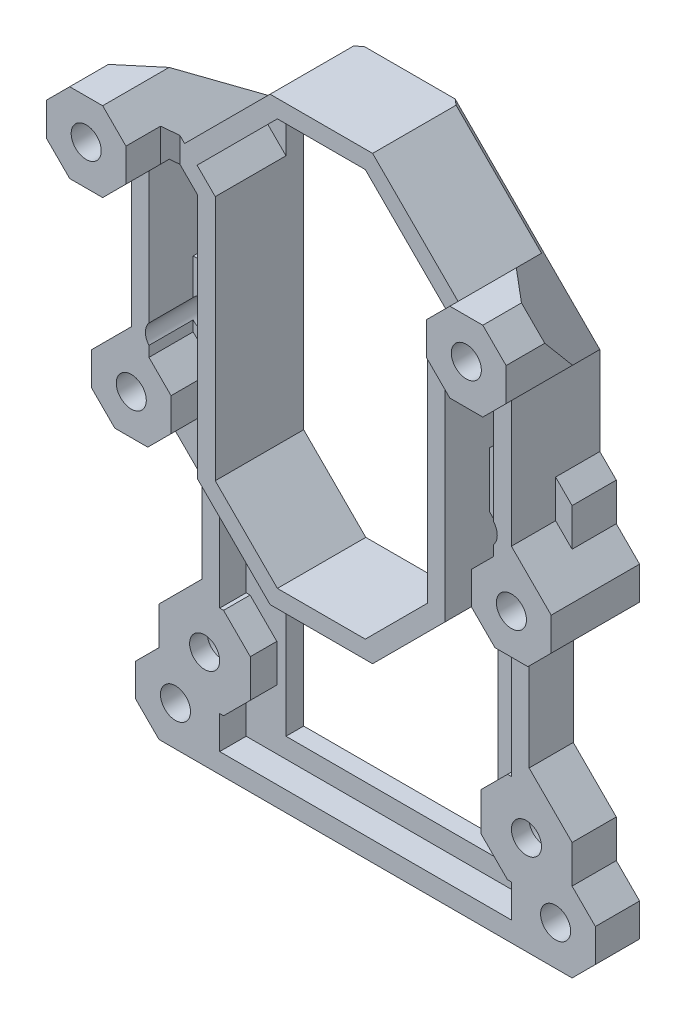
SolidWorks part; units mm, degrees
ref_plane "Front Plane" through (0, 0, 0) normal (0, 0, 1) x (1, 0, 0)
ref_plane "Top Plane" through (0, 0, 0) normal (0, 1, 0) x (1, 0, 0)
ref_plane "Right Plane" through (0, 0, 0) normal (1, 0, 0) x (0, 0, -1)
sketch "Sketch1" plane through (0, 0, 0) normal (0, 0, 1) x (1, 0, 0)
  line L0 (-21.5, 0) -> (21.5, 0) construction
  line L1 (21.5, 0) -> (21.5, 60) construction
  line L2 (21.5, 60) -> (-21.5, 60) construction
  line L3 (-21.5, 60) -> (-21.5, 0) construction
  line L4 (-21.5, 33) -> (21.5, 33) construction
  line L5 (0, 0) -> (0, 60) construction
  line L9 (-5.799, 20) -> (0, 20)
  line L12 (0, 60) -> (0, 76.4523) construction
  line L13 (0, 68) -> (-4.9706, 68)
  line L15 (-16.5, 34.364) -> (-16.5, 55) construction
  line L16 (-20.339, 11.8029) -> (-18.5, 13.6419)
  line L17 (-16.061, 11.8029) -> (-20.339, 11.8029)
  line L18 (-20.339, 11.8029) -> (-23.364, 8.778)
  line L19 (-23.364, 8.778) -> (-23.364, 4.5)
  line L20 (-23.364, 4.5) -> (-20.339, 1.475)
  line L21 (-20.339, 1.475) -> (-16.061, 1.475)
  line L23 (-13.036, 37.5) -> (-13.036, 41.778)
  line L24 (-13.036, 41.778) -> (-16.061, 44.8029)
  line L25 (-16.061, 44.8029) -> (-20.339, 44.8029)
  line L26 (-20.339, 44.8029) -> (-23.364, 41.778)
  line L27 (-23.364, 41.778) -> (-23.364, 37.5)
  line L28 (-23.364, 37.5) -> (-20.339, 34.475)
  line L29 (-20.339, 34.475) -> (-16.061, 34.475)
  line L30 (-16.061, 34.475) -> (-13.036, 37.5)
  line L31 (13.036, 37.5) -> (16.061, 34.475)
  line L32 (16.061, 34.475) -> (20.339, 34.475)
  line L33 (20.339, 34.475) -> (23.364, 37.5)
  line L34 (23.364, 37.5) -> (23.364, 41.778)
  line L35 (23.364, 41.778) -> (20.339, 44.8029)
  line L36 (20.339, 44.8029) -> (16.061, 44.8029)
  line L37 (16.061, 44.8029) -> (13.036, 41.778)
  line L38 (13.036, 41.778) -> (13.036, 37.5)
  line L39 (-14, 0) -> (-14, 51.1419) construction
  line L40 (-16.5, 0) -> (-16.5, 33.5294) construction
  line L41 (-17, 58.136) -> (-17, 61.864)
  line L42 (-17, 61.864) -> (-19.636, 64.5)
  line L43 (-19.636, 64.5) -> (-23.364, 64.5)
  line L44 (-23.364, 64.5) -> (-26, 61.864)
  line L45 (-26, 61.864) -> (-26, 58.136)
  line L46 (-26, 58.136) -> (-23.364, 55.5)
  line L47 (-23.364, 55.5) -> (-19.636, 55.5)
  line L48 (-19.636, 55.5) -> (-17, 58.136)
  line L49 (-23.364, 37.5) -> (-26, 34.864)
  line L50 (-26, 34.864) -> (-26, 31.136)
  line L51 (-26, 31.136) -> (-23.364, 28.5)
  line L52 (-23.364, 28.5) -> (-19.636, 28.5)
  line L53 (-19.636, 28.5) -> (-17, 31.136)
  line L54 (-17, 31.136) -> (-17, 34.864)
  line L55 (-17, 34.864) -> (-19.636, 37.5)
  line L56 (-19.636, 37.5) -> (-23.364, 37.5)
  line L57 (-23.364, 4.5) -> (-26, 1.864)
  line L58 (-26, 1.864) -> (-26, -1.864)
  line L59 (-26, -1.864) -> (-23.364, -4.5)
  line L60 (-23.364, -4.5) -> (-19.636, -4.5)
  line L61 (-19.636, -4.5) -> (-17, -1.864)
  line L62 (-17, -1.864) -> (-17, 1.864)
  line L63 (-17, 1.864) -> (-19.636, 4.5)
  line L64 (-19.636, 4.5) -> (-23.364, 4.5)
  line L65 (23.364, -4.5) -> (26, -1.864)
  line L66 (26, -1.864) -> (26, 1.864)
  line L67 (26, 1.864) -> (23.364, 4.5)
  line L68 (23.364, 4.5) -> (19.636, 4.5)
  line L69 (19.636, 4.5) -> (17, 1.864)
  line L70 (17, 1.864) -> (17, -1.864)
  line L71 (17, -1.864) -> (19.636, -4.5)
  line L72 (19.636, -4.5) -> (23.364, -4.5)
  line L73 (19.636, 28.5) -> (23.364, 28.5)
  line L74 (23.364, 28.5) -> (26, 31.136)
  line L75 (26, 31.136) -> (26, 34.864)
  line L76 (26, 34.864) -> (23.364, 37.5)
  line L77 (23.364, 37.5) -> (19.636, 37.5)
  line L78 (19.636, 37.5) -> (17, 34.864)
  line L79 (17, 34.864) -> (17, 31.136)
  line L80 (17, 31.136) -> (19.636, 28.5)
  line L81 (23.364, 64.5) -> (19.636, 64.5)
  line L82 (19.636, 64.5) -> (17, 61.864)
  line L83 (17, 61.864) -> (17, 58.136)
  line L84 (17, 58.136) -> (19.636, 55.5)
  line L85 (19.636, 55.5) -> (23.364, 55.5)
  line L86 (23.364, 55.5) -> (26, 58.136)
  line L87 (26, 58.136) -> (26, 61.864)
  line L88 (26, 61.864) -> (23.364, 64.5)
  line L89 (-12, 34) -> (-12, 68.1911) construction
  line L90 (12, 34) -> (12, 71.0139) construction
  line L91 (0, -4.5) -> (-19.636, -4.5)
  line L94 (0, -2.25) -> (-16.5, -2.25)
  line L95 (-16.5, -2.25) -> (-16.5, 34.364)
  line L97 (0, -4.5) -> (0, 0) construction
  line L100 (-4.9706, 22) -> (0, 22)
  line L101 (0, -2.25) -> (-16.5, -2.25) construction
  line L102 (-17, 61.864) -> (-12, 56.864)
  line L103 (-12, 56.864) -> (-12, 29.0294)
  line L105 (-4.9706, 68) -> (-14.0533, 58.9173)
  line L106 (-23.364, 55.5) -> (-21.5, 53.636)
  line L107 (-23.364, 37.5) -> (-21.5, 39.364)
  line L108 (-21.5, 39.364) -> (-21.5, 53.636)
  line L109 (-23.364, 4.5) -> (-18.5, 9.364)
  line L110 (-18.5, 9.364) -> (-18.5, 23.636)
  line L111 (-18.5, 23.636) -> (-23.364, 28.5)
  line L115 (-16.5, -4.5) -> (-16.5, 0) construction
  line L116 (-16.5503, 58.5858) -> (-14, 56.0355)
  line L117 (-14, 56.0355) -> (-14, 28.201)
  line L119 (-17, 34.864) -> (-16.5, 34.364)
  line L120 (-19.636, 37.5) -> (-19.5, 37.364)
  line L121 (-19.5, 37.364) -> (-19.5, 55.636)
  line L122 (-19.5, 55.636) -> (-19.636, 55.5)
  line L123 (-17, 58.136) -> (-16.5503, 58.5858)
  line L124 (-19.636, 55.5) -> (-19.5, 55.636)
  line L126 (-16.061, 1.475) -> (-13.036, 4.5)
  line L128 (-12, 50.5) -> (-33.4283, 71.9283) construction
  line L129 (0, 70) -> (-5.799, 70)
  line L130 (-5.799, 70) -> (-15.4675, 60.3315)
  line L131 (-4.9706, 22) -> (-12, 29.0294)
  line L132 (-12, 26.201) -> (-12, 0)
  line L133 (0, 0) -> (-12, 0)
  line L134 (-12, 26.201) -> (-5.799, 20)
  line L135 (-12, 26.201) -> (-14, 28.201)
  line L136 (-13.036, 4.5) -> (-13.036, 8.778)
  line L137 (-13.036, 8.778) -> (-16.061, 11.8029)
  circle A0 centre (-21.5, 60) radius 1.7
  circle A1 centre (-21.5, 33) radius 1.7
  circle A2 centre (-21.5, 0) radius 1.7
  circle A3 centre (21.5, 0) radius 1.7
  circle A4 centre (21.5, 33) radius 1.7
  circle A5 centre (21.5, 60) radius 1.7
  circle A7 centre (-18.2, 6.639) radius 1.7
  circle A8 centre (-18.2, 39.639) radius 1.7
  circle A9 centre (18.2, 39.639) radius 1.7
  circle A10 centre (0, 34) radius 12 construction
  circle A11 centre (0, 56) radius 12 construction
  circle A12 centre (-18.2, 39.639) radius 3
  circle A13 centre (-18.2, 39.639) radius 5.164 construction
  circle A14 centre (18.2, 39.639) radius 5.164 construction
  circle A15 centre (-21.5, 60) radius 4.5 construction
  circle A16 centre (-21.5, 33) radius 4.5 construction
  circle A17 centre (-21.5, 0) radius 4.5 construction
  circle A18 centre (21.5, 0) radius 4.5 construction
  circle A19 centre (21.5, 33) radius 4.5 construction
  circle A20 centre (21.5, 60) radius 4.5 construction
  circle A21 centre (-18.2, 6.639) radius 3
  circle A22 centre (-18.2, 6.639) radius 5.164 construction
  dimension "D4" = 3.4
  dimension "D5" = 24
  dimension "D7" = 2
  dimension "D8" = 6
  dimension "D9" = 9
  dimension "D10" = 9
  dimension "D11" = 9
  dimension "D12" = 9
  dimension "D13" = 9
  dimension "D14" = 9
  dimension "D1" = 43
  dimension "D2" = 33
  dimension "D3" = 27
  dimension "D15" = 2.5
  dimension "D16" = 2
  dimension "D17" = 2
  dimension "D19" = 135
  dimension "D20" = 2.25
  dimension "D21" = 2
  dimension "D22" = 2
  dimension "D23" = 2
  dimension "D24" = 34
  dimension "D25" = 2
  dimension "D26" = 22
  dimension "D27" = 2
  dimension "D28" = 2
sketch "Sketch5" plane through (0, 0, 0) normal (0, 0, 1) x (1, 0, 0)
  line L102 (0, -4.5) -> (-19.636, -4.5) construction
  line L103 (-23.364, -4.5) -> (-19.636, -4.5) construction
  line L104 (-26, -1.864) -> (-23.364, -4.5) construction
  line L105 (-26, 1.864) -> (-26, -1.864) construction
  line L106 (-23.364, 4.5) -> (-26, 1.864) construction
  line L107 (-23.364, 8.778) -> (-23.364, 4.5) construction
  line L108 (-20.339, 11.8029) -> (-23.364, 8.778) construction
  line L109 (-20.339, 11.8029) -> (-18.5, 13.6419) construction
  line L110 (-18.5, 9.364) -> (-18.5, 23.636) construction
  line L111 (-18.5, 23.636) -> (-23.364, 28.5) construction
  line L112 (-26, 31.136) -> (-23.364, 28.5) construction
  line L113 (-26, 34.864) -> (-26, 31.136) construction
  line L114 (-23.364, 37.5) -> (-26, 34.864) construction
  line L115 (-23.364, 41.778) -> (-23.364, 37.5) construction
  line L116 (-20.339, 44.8029) -> (-23.364, 41.778) construction
  line L117 (-21.5, 39.364) -> (-21.5, 53.636) construction
  line L118 (-23.364, 55.5) -> (-21.5, 53.636) construction
  line L119 (-26, 58.136) -> (-23.364, 55.5) construction
  line L120 (-26, 61.864) -> (-26, 58.136) construction
  line L121 (-23.364, 64.5) -> (-26, 61.864) construction
  line L122 (-19.636, 64.5) -> (-23.364, 64.5) construction
  line L123 (-17, 61.864) -> (-19.636, 64.5) construction
  line L124 (-17, 61.864) -> (-12, 56.864) construction
  line L125 (-5.799, 70) -> (-15.4675, 60.3315) construction
  line L126 (0, 70) -> (-5.799, 70) construction
  line L127 (0, 68) -> (-4.9706, 68) construction
  line L128 (-4.9706, 68) -> (-14.0533, 58.9173) construction
  line L129 (-12, 56.864) -> (-12, 29.0294) construction
  line L130 (-4.9706, 22) -> (-12, 29.0294) construction
  line L131 (-4.9706, 22) -> (0, 22) construction
  line L132 (-5.799, 20) -> (0, 20) construction
  line L133 (-12, 26.201) -> (-5.799, 20) construction
  line L134 (-12, 26.201) -> (-12, 0) construction
  line L135 (0, 0) -> (-12, 0) construction
  line L136 (0, 0) -> (0, 60) construction
  line L137 (0, 60) -> (0, 76.4523) construction
  line L138 (0, -4.5) -> (0, 0) construction
  line L139 (19.636, -4.5) -> (-19.636, -4.5)
  line L140 (-23.364, -4.5) -> (-19.636, -4.5)
  line L141 (-26, -1.864) -> (-23.364, -4.5)
  line L142 (-26, 1.864) -> (-26, -1.864)
  line L143 (-23.364, 4.5) -> (-26, 1.864)
  line L144 (-23.364, 8.778) -> (-23.364, 4.5)
  line L145 (-20.339, 11.8029) -> (-23.364, 8.778)
  line L146 (-20.339, 11.8029) -> (-18.5, 13.6419)
  line L147 (-18.5, 13.6419) -> (-18.5, 23.636)
  line L148 (-18.5, 23.636) -> (-23.364, 28.5)
  line L149 (-26, 31.136) -> (-23.364, 28.5)
  line L150 (-26, 34.864) -> (-26, 31.136)
  line L151 (-23.364, 37.5) -> (-26, 34.864)
  line L152 (-23.364, 41.778) -> (-23.364, 37.5)
  line L153 (-21.5, 43.6419) -> (-23.364, 41.778)
  line L154 (-21.5, 43.6419) -> (-21.5, 53.636)
  line L155 (-23.364, 55.5) -> (-21.5, 53.636)
  line L156 (-26, 58.136) -> (-23.364, 55.5)
  line L157 (-26, 61.864) -> (-26, 58.136)
  line L158 (-23.364, 64.5) -> (-26, 61.864)
  line L159 (-19.636, 64.5) -> (-23.364, 64.5)
  line L160 (-17, 61.864) -> (-19.636, 64.5)
  line L161 (-17, 61.864) -> (-15.4675, 60.3315)
  line L162 (-5.799, 70) -> (-15.4675, 60.3315)
  line L163 (5.799, 70) -> (-5.799, 70)
  line L164 (4.9706, 68) -> (-4.9706, 68)
  line L165 (-4.9706, 68) -> (-12, 60.9706)
  line L166 (-12, 34) -> (-12, 29.0294)
  line L167 (-4.9706, 22) -> (-12, 29.0294)
  line L168 (-4.9706, 22) -> (4.9706, 22)
  line L169 (-5.799, 20) -> (5.799, 20)
  line L170 (-12, 26.201) -> (-5.799, 20)
  line L171 (-12, 26.201) -> (-12, 0)
  line L172 (12, 0) -> (-12, 0)
  line L173 (0, 0) -> (0, 60) construction
  line L174 (0, 60) -> (0, 76.4523) construction
  line L175 (0, -4.5) -> (0, 0) construction
  line L176 (12, 56.864) -> (12, 60.9706)
  line L177 (-12, 34) -> (-12, 68.1911) construction
  line L178 (-12, 34) -> (-12, 60.9706)
  line L179 (12, 26.201) -> (12, 0)
  line L180 (12, 26.201) -> (5.799, 20)
  line L181 (4.9706, 22) -> (12, 29.0294)
  line L182 (12, 56.864) -> (12, 29.0294)
  line L183 (4.9706, 68) -> (12, 60.9706)
  line L184 (5.799, 70) -> (15.4675, 60.3315)
  line L185 (17, 61.864) -> (15.4675, 60.3315)
  line L186 (17, 61.864) -> (19.636, 64.5)
  line L187 (19.636, 64.5) -> (23.364, 64.5)
  line L188 (23.364, 64.5) -> (26, 61.864)
  line L189 (26, 61.864) -> (26, 58.136)
  line L190 (26, 58.136) -> (23.364, 55.5)
  line L191 (23.364, 55.5) -> (21.5, 53.636)
  line L192 (21.5, 43.6419) -> (21.5, 53.636)
  line L193 (21.5, 43.6419) -> (23.364, 41.778)
  line L194 (23.364, 41.778) -> (23.364, 37.5)
  line L195 (23.364, 37.5) -> (26, 34.864)
  line L196 (26, 34.864) -> (26, 31.136)
  line L197 (26, 31.136) -> (23.364, 28.5)
  line L198 (18.5, 23.636) -> (23.364, 28.5)
  line L199 (18.5, 13.6419) -> (18.5, 23.636)
  line L200 (20.339, 11.8029) -> (18.5, 13.6419)
  line L201 (20.339, 11.8029) -> (23.364, 8.778)
  line L202 (23.364, 8.778) -> (23.364, 4.5)
  line L203 (23.364, 4.5) -> (26, 1.864)
  line L204 (26, 1.864) -> (26, -1.864)
  line L205 (26, -1.864) -> (23.364, -4.5)
  line L206 (23.364, -4.5) -> (19.636, -4.5)
  circle A8 centre (-18.2, 39.639) radius 1.7 construction
  circle A9 centre (-18.2, 6.639) radius 1.7 construction
  circle A10 centre (-18.2, 39.639) radius 1.7
  circle A11 centre (-18.2, 6.639) radius 1.7
  circle A12 centre (18.2, 6.639) radius 1.7
  circle A13 centre (18.2, 39.639) radius 1.7
extrude "Boss-Extrude1" add sketch "Sketch5" along normal blind 2
sketch "Sketch9" plane through (0, 0, 2) normal (0, 0, 1) x (1, 0, 0)
  line L73 (0, 70) -> (-5.799, 70) construction
  line L76 (0, 60) -> (0, 76.4523) construction
  line L77 (0, 0) -> (0, 60) construction
  line L78 (0, -4.5) -> (0, 0) construction
  line L79 (0, 68) -> (-4.9706, 68) construction
  line L80 (-4.9706, 68) -> (-14.0533, 58.9173) construction
  line L81 (-5.799, 70) -> (-15.4675, 60.3315) construction
  line L82 (-17, 61.864) -> (-12, 56.864) construction
  line L83 (-17, 61.864) -> (-19.636, 64.5) construction
  line L84 (-19.636, 64.5) -> (-23.364, 64.5) construction
  line L85 (-23.364, 64.5) -> (-26, 61.864) construction
  line L86 (-26, 61.864) -> (-26, 58.136) construction
  line L87 (-26, 58.136) -> (-23.364, 55.5) construction
  line L88 (-23.364, 55.5) -> (-21.5, 53.636) construction
  line L89 (-21.5, 39.364) -> (-21.5, 53.636) construction
  line L90 (-20.339, 44.8029) -> (-23.364, 41.778) construction
  line L91 (-23.364, 41.778) -> (-23.364, 37.5) construction
  line L92 (-23.364, 37.5) -> (-26, 34.864) construction
  line L93 (-26, 34.864) -> (-26, 31.136) construction
  line L94 (-26, 31.136) -> (-23.364, 28.5) construction
  line L95 (-18.5, 23.636) -> (-23.364, 28.5) construction
  line L97 (-20.339, 11.8029) -> (-18.5, 13.6419) construction
  line L98 (-20.339, 11.8029) -> (-23.364, 8.778) construction
  line L99 (-23.364, 8.778) -> (-23.364, 4.5) construction
  line L100 (-23.364, 4.5) -> (-26, 1.864) construction
  line L101 (-26, 1.864) -> (-26, -1.864) construction
  line L102 (-26, -1.864) -> (-23.364, -4.5) construction
  line L103 (-23.364, -4.5) -> (-19.636, -4.5) construction
  line L104 (0, -2.25) -> (-16.5, -2.25) construction
  line L105 (-16.5, -2.25) -> (-16.5, 34.364) construction
  line L106 (-12, 26.201) -> (-5.799, 20) construction
  line L107 (-5.799, 20) -> (0, 20) construction
  line L108 (-4.9706, 22) -> (0, 22) construction
  line L109 (-4.9706, 22) -> (-12, 29.0294) construction
  line L110 (-12, 26.201) -> (-14, 28.201) construction
  line L111 (-14, 56.0355) -> (-14, 28.201) construction
  line L112 (-12, 56.864) -> (-12, 29.0294) construction
  line L113 (-16.5503, 58.5858) -> (-14, 56.0355) construction
  line L114 (-17, 58.136) -> (-16.5503, 58.5858) construction
  line L115 (-19.636, 55.5) -> (-17, 58.136) construction
  line L117 (5.799, 70) -> (-5.799, 70)
  line L118 (0, 60) -> (0, 76.4523) construction
  line L119 (0, 0) -> (0, 60) construction
  line L120 (0, -4.5) -> (0, 0) construction
  line L121 (4.9706, 68) -> (-4.9706, 68)
  line L122 (-4.9706, 68) -> (-14.0533, 58.9173)
  line L123 (-5.799, 70) -> (-15.4675, 60.3315)
  line L124 (-17, 61.864) -> (-15.4675, 60.3315)
  line L127 (-17, 61.864) -> (-19.636, 64.5)
  line L128 (-19.636, 64.5) -> (-23.364, 64.5)
  line L129 (-23.364, 64.5) -> (-26, 61.864)
  line L130 (-26, 61.864) -> (-26, 58.136)
  line L131 (-26, 58.136) -> (-23.364, 55.5)
  line L132 (-23.364, 55.5) -> (-21.5, 53.636)
  line L133 (-21.5, 43.6419) -> (-21.5, 53.636)
  line L134 (-21.5, 43.6419) -> (-23.364, 41.778)
  line L135 (-23.364, 41.778) -> (-23.364, 37.5)
  line L136 (-23.364, 37.5) -> (-26, 34.864)
  line L137 (-26, 34.864) -> (-26, 31.136)
  line L138 (-26, 31.136) -> (-23.364, 28.5)
  line L139 (-18.5, 23.636) -> (-23.364, 28.5)
  line L140 (18.5, 13.6419) -> (18.5, 23.636)
  line L141 (-20.339, 11.8029) -> (-18.5, 13.6419)
  line L142 (-20.339, 11.8029) -> (-23.364, 8.778)
  line L143 (-23.364, 8.778) -> (-23.364, 4.5)
  line L144 (-23.364, 4.5) -> (-26, 1.864)
  line L145 (-26, 1.864) -> (-26, -1.864)
  line L146 (-26, -1.864) -> (-23.364, -4.5)
  line L147 (-23.364, -4.5) -> (-19.636, -4.5)
  line L149 (16.5, -2.25) -> (-16.5, -2.25)
  line L150 (-16.5, -2.25) -> (-16.5, 1.475)
  line L151 (-12, 26.201) -> (-5.799, 20)
  line L152 (-5.799, 20) -> (5.799, 20)
  line L153 (-4.9706, 22) -> (4.9706, 22)
  line L154 (-4.9706, 22) -> (-12, 29.0294)
  line L155 (-12, 26.201) -> (-14, 28.201)
  line L156 (-14, 56.0355) -> (-14, 42.7419)
  line L157 (-12, 56.864) -> (-12, 29.0294)
  line L158 (-16.5503, 58.5858) -> (-14, 56.0355)
  line L159 (-17, 58.136) -> (-16.5503, 58.5858)
  line L160 (-19.5, 55.636) -> (-17, 58.136)
  line L161 (-14, 36.536) -> (-14, 28.201)
  line L162 (-16.061, 44.8029) -> (-20.339, 44.8029) construction
  line L163 (-13.036, 41.778) -> (-16.061, 44.8029) construction
  line L164 (-16.061, 34.475) -> (-13.036, 37.5) construction
  line L165 (-20.339, 34.475) -> (-16.061, 34.475) construction
  line L166 (-16.061, 11.8029) -> (-20.339, 11.8029) construction
  line L167 (-13.036, 8.778) -> (-16.061, 11.8029) construction
  line L168 (-13.036, 4.5) -> (-13.036, 8.778) construction
  line L169 (-16.061, 1.475) -> (-13.036, 4.5) construction
  line L170 (-20.339, 1.475) -> (-16.061, 1.475) construction
  line L171 (-16.061, 44.8029) -> (-19.5, 44.8029)
  line L172 (-14, 42.7419) -> (-16.061, 44.8029)
  line L173 (-16.061, 34.475) -> (-14, 36.536)
  line L174 (-16.5, 34.475) -> (-16.061, 34.475)
  line L175 (-16.061, 11.8029) -> (-16.5, 11.8029)
  line L176 (-13.036, 8.778) -> (-16.061, 11.8029)
  line L177 (-13.036, 4.5) -> (-13.036, 8.778)
  line L178 (-16.061, 1.475) -> (-13.036, 4.5)
  line L179 (-16.5, 1.475) -> (-16.061, 1.475)
  line L180 (-14.0533, 58.9173) -> (-12, 56.864)
  line L181 (-19.5, 44.8029) -> (-19.5, 55.636)
  line L182 (-16.5, 11.8029) -> (-16.5, 34.475)
  line L183 (16.5, 11.8029) -> (16.5, 34.475)
  line L184 (-18.5, 13.6419) -> (-18.5, 23.636)
  line L185 (19.5, 44.8029) -> (19.5, 55.636)
  line L186 (14.0533, 58.9173) -> (12, 56.864)
  line L187 (16.5, 1.475) -> (16.061, 1.475)
  line L188 (16.061, 1.475) -> (13.036, 4.5)
  line L189 (13.036, 4.5) -> (13.036, 8.778)
  line L190 (13.036, 8.778) -> (16.061, 11.8029)
  line L191 (16.061, 11.8029) -> (16.5, 11.8029)
  line L192 (16.5, 34.475) -> (16.061, 34.475)
  line L193 (16.061, 34.475) -> (14, 36.536)
  line L194 (14, 42.7419) -> (16.061, 44.8029)
  line L195 (16.061, 44.8029) -> (19.5, 44.8029)
  line L196 (14, 36.536) -> (14, 28.201)
  line L197 (19.5, 55.636) -> (17, 58.136)
  line L198 (17, 58.136) -> (16.5503, 58.5858)
  line L199 (16.5503, 58.5858) -> (14, 56.0355)
  line L200 (12, 56.864) -> (12, 29.0294)
  line L201 (14, 56.0355) -> (14, 42.7419)
  line L202 (12, 26.201) -> (14, 28.201)
  line L203 (4.9706, 22) -> (12, 29.0294)
  line L204 (12, 26.201) -> (5.799, 20)
  line L205 (16.5, -2.25) -> (16.5, 1.475)
  line L206 (23.364, -4.5) -> (19.636, -4.5)
  line L207 (26, -1.864) -> (23.364, -4.5)
  line L208 (26, 1.864) -> (26, -1.864)
  line L209 (23.364, 4.5) -> (26, 1.864)
  line L210 (23.364, 8.778) -> (23.364, 4.5)
  line L211 (20.339, 11.8029) -> (23.364, 8.778)
  line L212 (20.339, 11.8029) -> (18.5, 13.6419)
  line L213 (18.5, 23.636) -> (23.364, 28.5)
  line L214 (26, 31.136) -> (23.364, 28.5)
  line L215 (26, 34.864) -> (26, 31.136)
  line L216 (23.364, 37.5) -> (26, 34.864)
  line L217 (23.364, 41.778) -> (23.364, 37.5)
  line L218 (21.5, 43.6419) -> (23.364, 41.778)
  line L219 (21.5, 43.6419) -> (21.5, 53.636)
  line L220 (23.364, 55.5) -> (21.5, 53.636)
  line L221 (26, 58.136) -> (23.364, 55.5)
  line L222 (26, 61.864) -> (26, 58.136)
  line L223 (23.364, 64.5) -> (26, 61.864)
  line L224 (19.636, 64.5) -> (23.364, 64.5)
  line L225 (17, 61.864) -> (19.636, 64.5)
  line L226 (17, 61.864) -> (15.4675, 60.3315)
  line L227 (5.799, 70) -> (15.4675, 60.3315)
  line L228 (4.9706, 68) -> (14.0533, 58.9173)
  line L229 (0, -4.5) -> (-19.636, -4.5) construction
  line L230 (19.636, -4.5) -> (-19.636, -4.5)
  circle A2 centre (-21.5, 0) radius 1.7 construction
  circle A5 centre (-21.5, 33) radius 1.7 construction
  circle A6 centre (-18.2, 39.639) radius 1.7 construction
  circle A7 centre (-18.2, 6.639) radius 1.7 construction
  circle A10 centre (-21.5, 0) radius 1.7
  circle A12 centre (-21.5, 33) radius 1.7
  circle A13 centre (-18.2, 39.639) radius 1.7
  circle A14 centre (-18.2, 6.639) radius 1.7
  circle A15 centre (18.2, 6.639) radius 1.7
  circle A16 centre (18.2, 39.639) radius 1.7
  circle A17 centre (21.5, 33) radius 1.7
  circle A18 centre (21.5, 0) radius 1.7
extrude "Boss-Extrude3" add sketch "Sketch9" along normal blind 3
sketch "Sketch10" plane through (0, 0, 5) normal (0, 0, 1) x (1, 0, 0)
  line L0 (19.5, 40.7344) -> (19.5, 55.636)
  line L1 (-19.5, 40.7344) -> (-19.5, 55.636)
  line L21 (0, 68) -> (-4.9706, 68) construction
  line L30 (0, 60) -> (0, 76.4523) construction
  line L31 (0, 0) -> (0, 60) construction
  line L32 (0, -4.5) -> (0, 0) construction
  line L33 (-4.9706, 68) -> (-14.0533, 58.9173) construction
  line L34 (-17, 61.864) -> (-12, 56.864) construction
  line L35 (-12, 56.864) -> (-12, 29.0294) construction
  line L36 (-4.9706, 22) -> (-12, 29.0294) construction
  line L37 (-4.9706, 22) -> (0, 22) construction
  line L38 (-5.799, 20) -> (0, 20) construction
  line L39 (-12, 26.201) -> (-5.799, 20) construction
  line L40 (-12, 26.201) -> (-14, 28.201) construction
  line L41 (-14, 56.0355) -> (-14, 28.201) construction
  line L42 (-16.5503, 58.5858) -> (-14, 56.0355) construction
  line L43 (-17, 61.864) -> (-19.636, 64.5) construction
  line L45 (-19.636, 64.5) -> (-23.364, 64.5) construction
  line L46 (-23.364, 64.5) -> (-26, 61.864) construction
  line L47 (-26, 61.864) -> (-26, 58.136) construction
  line L48 (-26, 58.136) -> (-23.364, 55.5) construction
  line L50 (4.9706, 68) -> (-4.9706, 68)
  line L52 (0, 60) -> (0, 76.4523) construction
  line L53 (0, 0) -> (0, 60) construction
  line L54 (0, -4.5) -> (0, 0) construction
  line L58 (-4.9706, 68) -> (-14.0533, 58.9173)
  line L61 (-12, 56.864) -> (-12, 29.0294)
  line L62 (-4.9706, 22) -> (-12, 29.0294)
  line L63 (-4.9706, 22) -> (4.9706, 22)
  line L64 (-5.799, 20) -> (5.799, 20)
  line L65 (-12, 26.201) -> (-5.799, 20)
  line L66 (-12, 26.201) -> (-14, 28.201)
  line L67 (-14, 56.0355) -> (-14, 28.201)
  line L68 (-16.5503, 58.5858) -> (-14, 56.0355)
  line L69 (-17, 61.864) -> (-19.636, 64.5)
  line L70 (-19.636, 64.5) -> (-23.364, 64.5)
  line L71 (-23.364, 64.5) -> (-26, 61.864)
  line L72 (-26, 61.864) -> (-26, 58.136)
  line L73 (-26, 58.136) -> (-23.364, 55.5)
  line L74 (-17, 34.864) -> (-19.636, 37.5) construction
  line L75 (-23.364, 55.5) -> (-21.5, 53.636) construction
  line L76 (-21.5, 39.364) -> (-21.5, 53.636) construction
  line L79 (-23.364, 37.5) -> (-26, 34.864) construction
  line L80 (-26, 34.864) -> (-26, 31.136) construction
  line L81 (-26, 31.136) -> (-23.364, 28.5) construction
  line L82 (-23.364, 28.5) -> (-19.636, 28.5) construction
  line L83 (-19.636, 28.5) -> (-17, 31.136) construction
  line L84 (-17, 31.136) -> (-17, 34.864) construction
  line L85 (-23.364, 55.5) -> (-21.5, 53.636)
  line L86 (21.5, 39.364) -> (21.5, 53.636)
  line L87 (23.364, 37.5) -> (21.5, 39.364)
  line L89 (-23.364, 37.5) -> (-26, 34.864)
  line L90 (-26, 34.864) -> (-26, 31.136)
  line L91 (-26, 31.136) -> (-23.364, 28.5)
  line L92 (-23.364, 28.5) -> (-19.636, 28.5)
  line L93 (-19.636, 28.5) -> (-17, 31.136)
  line L94 (-17, 31.136) -> (-17, 34.864)
  line L95 (-19.5, 37.364) -> (-19.5, 55.636) construction
  line L96 (-19.636, 55.5) -> (-17, 58.136) construction
  line L97 (-17, 58.136) -> (-16.5503, 58.5858) construction
  line L98 (-17, 34.864) -> (-19.5, 37.364)
  line L99 (-19.5, 37.364) -> (-19.5, 38.5435)
  line L100 (-19.5, 55.636) -> (-17, 58.136)
  line L101 (-17, 58.136) -> (-16.5503, 58.5858)
  line L102 (0, 70) -> (-5.799, 70) construction
  line L103 (-5.799, 70) -> (-15.4675, 60.3315) construction
  line L104 (5.799, 70) -> (-5.799, 70)
  line L105 (-5.799, 70) -> (-15.4675, 60.3315)
  line L106 (-17, 61.864) -> (-15.4675, 60.3315)
  line L107 (-14.0533, 58.9173) -> (-12, 56.864)
  line L108 (-23.364, 37.5) -> (-21.5, 39.364) construction
  line L109 (-23.364, 37.5) -> (-21.5, 39.364)
  line L110 (-21.5, 39.364) -> (-21.5, 53.636)
  line L111 (17, 61.864) -> (15.4675, 60.3315)
  line L112 (5.799, 70) -> (15.4675, 60.3315)
  line L113 (17, 58.136) -> (16.5503, 58.5858)
  line L114 (19.5, 55.636) -> (17, 58.136)
  line L115 (19.5, 37.364) -> (19.5, 38.5435)
  line L116 (17, 34.864) -> (19.5, 37.364)
  line L117 (17, 31.136) -> (17, 34.864)
  line L118 (19.636, 28.5) -> (17, 31.136)
  line L119 (23.364, 28.5) -> (19.636, 28.5)
  line L120 (26, 31.136) -> (23.364, 28.5)
  line L121 (26, 34.864) -> (26, 31.136)
  line L122 (23.364, 37.5) -> (26, 34.864)
  line L123 (23.364, 55.5) -> (21.5, 53.636)
  line L124 (26, 58.136) -> (23.364, 55.5)
  line L125 (26, 61.864) -> (26, 58.136)
  line L126 (23.364, 64.5) -> (26, 61.864)
  line L127 (19.636, 64.5) -> (23.364, 64.5)
  line L128 (17, 61.864) -> (19.636, 64.5)
  line L129 (16.5503, 58.5858) -> (14, 56.0355)
  line L130 (14, 56.0355) -> (14, 28.201)
  line L131 (12, 26.201) -> (14, 28.201)
  line L132 (12, 26.201) -> (5.799, 20)
  line L133 (4.9706, 22) -> (12, 29.0294)
  line L134 (12, 56.864) -> (12, 29.0294)
  line L135 (14.0533, 58.9173) -> (12, 56.864)
  line L136 (4.9706, 68) -> (14.0533, 58.9173)
  circle A0 centre (-18.2, 39.639) radius 1.7 construction
  circle A1 centre (-21.5, 33) radius 1.7 construction
  circle A2 centre (-21.5, 33) radius 1.7
  circle A3 centre (21.5, 33) radius 1.7
  arc A4 (-19.5, 40.7344) -> (-19.5, 38.5435) centre (-18.2, 39.639) ccw
  circle A5 centre (18.2, 39.639) radius 1.7 construction
  arc A6 (19.5, 38.5435) -> (19.5, 40.7344) centre (18.2, 39.639) ccw
extrude "Boss-Extrude4" add sketch "Sketch10" along normal blind 5
sketch "Sketch12" plane through (0, 0, 10) normal (0, 0, 1) x (1, 0, 0)
  line L0 (-26, 58.136) -> (-23.364, 55.5) construction
  line L1 (-26, 61.864) -> (-26, 58.136) construction
  line L2 (-23.364, 64.5) -> (-26, 61.864) construction
  line L3 (-19.636, 64.5) -> (-23.364, 64.5) construction
  line L4 (-17, 61.864) -> (-19.636, 64.5) construction
  line L5 (-17, 58.136) -> (-17, 61.864) construction
  line L6 (-19.636, 55.5) -> (-17, 58.136) construction
  line L7 (-23.364, 55.5) -> (-19.636, 55.5) construction
  line L8 (-26, 58.136) -> (-23.364, 55.5)
  line L9 (-26, 61.864) -> (-26, 58.136)
  line L10 (-23.364, 64.5) -> (-26, 61.864)
  line L11 (-19.636, 64.5) -> (-23.364, 64.5)
  line L12 (-17, 61.864) -> (-19.636, 64.5)
  line L13 (-17, 58.136) -> (-17, 61.864)
  line L14 (-19.636, 55.5) -> (-17, 58.136)
  line L15 (-23.364, 55.5) -> (-19.636, 55.5)
  line L16 (0, 0) -> (0, 60) construction
  line L17 (0, 0) -> (0, 60) construction
  line L18 (17, 58.136) -> (17, 61.864)
  line L19 (17, 61.864) -> (19.636, 64.5)
  line L20 (19.636, 64.5) -> (23.364, 64.5)
  line L21 (23.364, 64.5) -> (26, 61.864)
  line L22 (26, 61.864) -> (26, 58.136)
  line L23 (26, 58.136) -> (23.364, 55.5)
  line L24 (23.364, 55.5) -> (19.636, 55.5)
  line L25 (19.636, 55.5) -> (17, 58.136)
extrude "Boss-Extrude5" add sketch "Sketch12" along normal blind 5.1
ref_plane "Plane1" through (19.25, 19.25, 0) normal (0.7071, 0.7071, 0) x (0, 0, -1)
ref_plane "Plane2" through (-19.25, 19.25, 0) normal (-0.7071, 0.7071, 0) x (0, 0, 1)
sketch "Sketch13" plane through (0, 0, 15.1) normal (0, 0, 1) x (1, 0, 0)
  line L0 (0, 0) -> (0, 60) construction
  line L1 (0, 0) -> (0, 60) construction
  circle A0 centre (-21.5, 60) radius 1.7 construction
  circle A1 centre (-21.5, 60) radius 1.7
  circle A2 centre (21.5, 60) radius 1.7
extrude "Suspension Dowels" cut sketch "Sketch13" against normal blind 3.75
sketch "Sketch15" plane through (19.25, 19.25, 0) normal (0.7071, 0.7071, 0) x (0, 0, -1)
  line L0 (0, 53.1292) -> (-15.3209, 65.985)
  line L1 (-15.3209, 65.985) -> (-8.893, 73.6454)
  line L2 (-8.893, 73.6454) -> (6.4279, 60.7896)
  line L3 (6.4279, 60.7896) -> (0, 53.1292)
  line L4 (0, 44.1942) -> (0, 74.4983) construction
  dimension "D1" = 20
  dimension "D2" = 10
  dimension "D3" = 50
extrude "Top Angle 1" cut sketch "Sketch15" against normal mid plane 50
sketch "Sketch16" plane through (-19.25, 19.25, 0) normal (-0.7071, 0.7071, 0) x (0, 0, 1)
  line L0 (0, 53.1292) -> (15.3209, 65.985)
  line L1 (15.3209, 65.985) -> (8.893, 73.6454)
  line L2 (8.893, 73.6454) -> (-6.4279, 60.7896)
  line L3 (-6.4279, 60.7896) -> (0, 53.1292)
  line L7 (0, 55.7652) -> (0, 59.4932) construction
  dimension "D1" = 50
  dimension "D2" = 20
  dimension "D3" = 10
extrude "Top Angle 2" cut sketch "Sketch16" against normal mid plane 50
chamfer "Chamfer1" distance 1 angle 50 8 edges at (18.0251, 57.1109, 2) (-18.0251, 57.1109, 2) (17, 60, 10) (-17, 60, 10) (21.5, 55.5, 10) (-21.5, 55.5, 10) (21.5, 28.5, 5) (-21.5, 28.5, 5)
sketch "Sketch18" plane through (0, 0, 0) normal (0, 0, -1) x (-1, 0, 0)
  line L0 (0, 0) -> (0, 60) construction
  line L1 (0, 0) -> (0, 60) construction
  circle A0 centre (18.2, 39.639) radius 3 construction
  circle A1 centre (18.2, 6.639) radius 3 construction
  circle A2 centre (18.2, 39.639) radius 3
  circle A3 centre (18.2, 6.639) radius 3
  circle A4 centre (-18.2, 39.639) radius 3
  circle A5 centre (-18.2, 6.639) radius 3
extrude "M3 Head Holes" cut sketch "Sketch18" against normal blind 3
ref_plane "Print Support Plane" through (0, 0, 3) normal (0, 0, -1) x (-1, 0, 0)
sketch "Sketch17" plane through (0, 0, 3) normal (0, 0, -1) x (-1, 0, 0)
  circle A0 centre (18.2, 39.639) radius 1.7 construction
  circle A1 centre (18.2, 6.639) radius 1.7 construction
  circle A2 centre (-18.2, 6.639) radius 1.7 construction
  circle A3 centre (-18.2, 39.639) radius 1.7 construction
  circle A4 centre (18.2, 39.639) radius 1.7
  circle A5 centre (18.2, 6.639) radius 1.7
  circle A6 centre (-18.2, 6.639) radius 1.7
  circle A7 centre (-18.2, 39.639) radius 1.7
extrude "Support Material" [suppressed] add sketch "Sketch17" against normal blind 0.3
